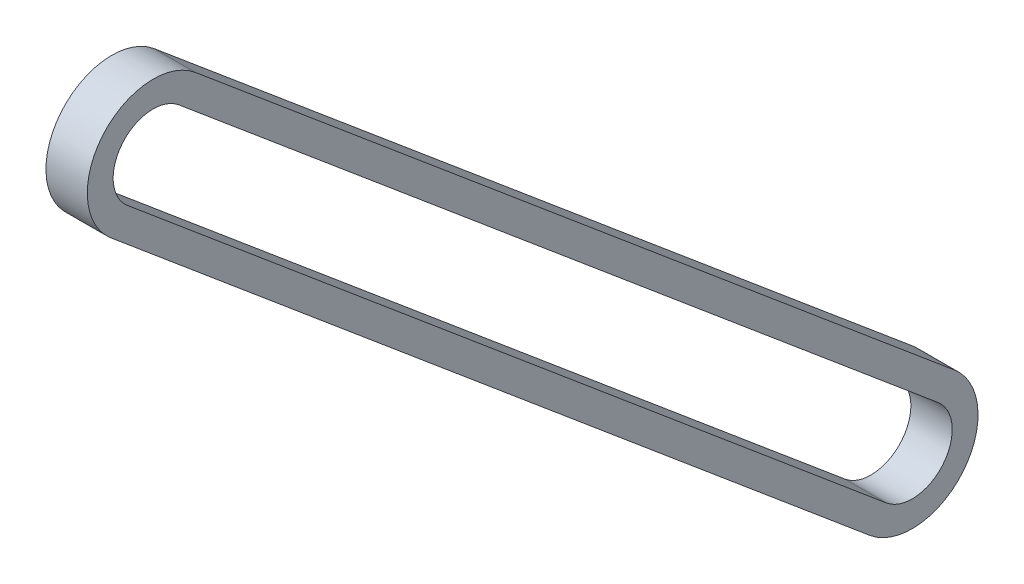
SolidWorks part; units mm, degrees
material "Rubber"
ref_plane "Front Plane" through (0, 0, 0) normal (0, 0, 1) x (1, 0, 0)
ref_plane "Top Plane" through (0, 0, 0) normal (0, 1, 0) x (1, 0, 0)
ref_plane "Right Plane" through (0, 0, 0) normal (1, 0, 0) x (0, 0, -1)
sketch "Sketch1" plane through (5.1882, 0, 0) normal (-1, 0, 0) x (0, 0, 1)
  line L0 (7.1353, -6.5683) -> (-22.2545, -31.241)
  line L1 (-18.9753, -35.1471) -> (10.4145, -10.4744)
  line L3 (9.7715, -9.7085) -> (-19.6183, -34.3812)
  line L4 (-21.6115, -32.0069) -> (7.7783, -7.3342)
  line L5 (-22.2545, -31.241) -> (-18.9753, -35.1471) construction
  circle A0 centre (8.7749, -8.5214) radius 1.55 construction
  circle A1 centre (-20.6149, -33.194) radius 1.55 construction
  circle A2 centre (8.7749, -8.5214) radius 1.55
  circle A3 centre (-20.6149, -33.194) radius 1.55
  arc A4 (-22.2545, -31.241) -> (-18.9753, -35.1471) centre (-20.6149, -33.194) ccw
  arc A5 (10.4145, -10.4744) -> (7.1353, -6.5683) centre (8.7749, -8.5214) ccw
  line M4 (4.9569, -0.2804) -> (4.008, -16.2523)
  line M6 (10.3469, -16.6289) -> (11.2957, -0.657)
  dimension "D1" = 1
extrude "Boss-Extrude1" add sketch "Sketch1" along normal blind 1.6 contours L0 A4 L1 L3 A3 L4 M4 | L5 A4 A3 | L3 L5 L1 M4 | L0 L5 L4 M4 | A5 M6
